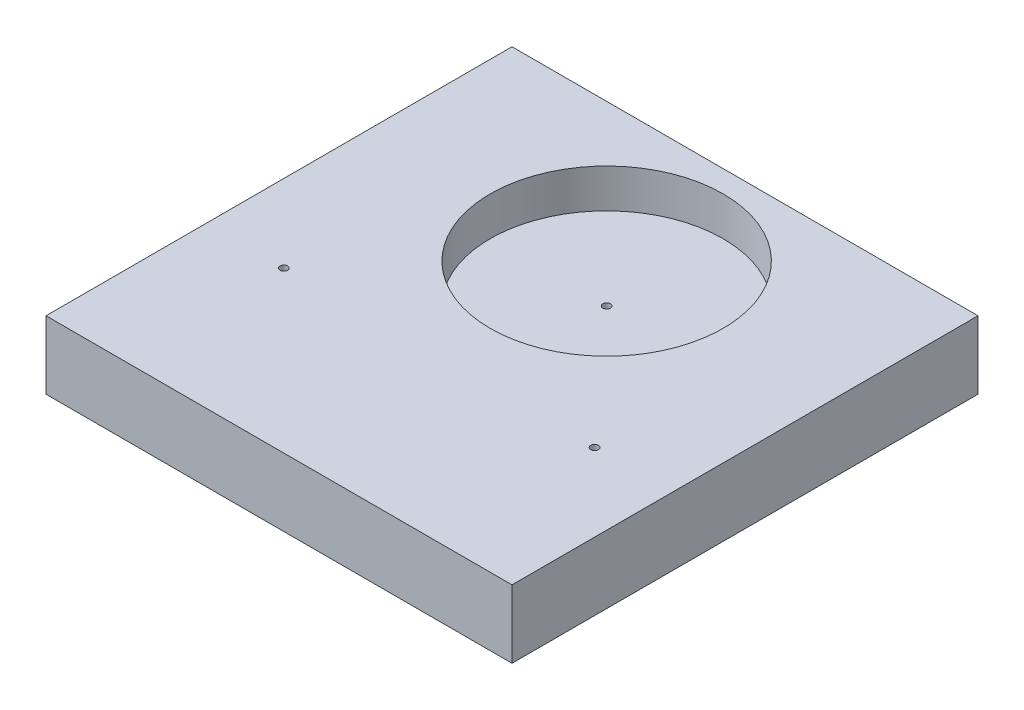
SolidWorks part; units mm, degrees
ref_plane "Front Plane" through (0, 0, 0) normal (0, 0, 1) x (1, 0, 0)
ref_plane "Top Plane" through (0, 0, 0) normal (0, 1, 0) x (1, 0, 0)
ref_plane "Right Plane" through (0, 0, 0) normal (1, 0, 0) x (0, 0, -1)
sketch "Sketch1" plane through (0, 0, 0) normal (0, 0, 1) x (1, 0, 0)
  line L7 (-76.2, -11.1125) -> (76.2, -11.1125)
  line L8 (-76.2, -11.1125) -> (-76.2, 11.1125)
  line L9 (-76.2, 11.1125) -> (76.2, 11.1125)
  line L10 (76.2, -11.1125) -> (76.2, 11.1125)
  line L11 (-76.2, -11.1125) -> (76.2, 11.1125) construction
  line L12 (-76.2, 11.1125) -> (76.2, -11.1125) construction
  point P4 (0, 0)
  point P14 (0, 0)
  dimension "Thickness" = 22.225
  dimension "Width" = 152.4
sketch "Sketch2" plane through (0, 0, 0) normal (0, 1, 0) x (0, 0, -1)
  line L0 (76.2, 76.2) -> (-76.2, 76.2) construction
  point P4 (0, 76.2)
  dimension "Length" = 152.4
sketch "Sketch3" plane through (0, 0, 0) normal (0, 0, 1) x (1, 0, 0)
  line L6 (-76.2, 11.1125) -> (76.2, 11.1125)
  line L7 (76.2, 11.1125) -> (76.2, -11.1125)
  line L8 (76.2, -11.1125) -> (-76.2, -11.1125)
  line L9 (-76.2, -11.1125) -> (-76.2, 11.1125)
extrude "Boss-Extrude1" add sketch "Sketch3" along normal mid plane 152.4
sketch "Feet" plane through (0, -11.1125, 0) normal (0, -1, 0) x (1, 0, 0)
  line L0 (-76.2, 76.2) -> (76.2, 76.2) construction
  line L1 (-76.2, 76.2) -> (-76.2, -76.2) construction
  line L2 (0, 76.2) -> (0, -76.2) construction
  line L3 (-76.2, -76.2) -> (76.2, -76.2) construction
  line L4 (-76.2, 0) -> (76.2, 0) construction
  line L5 (76.2, 76.2) -> (76.2, -76.2) construction
  circle A0 centre (-63.5, 63.5) radius 6.35
  circle A1 centre (63.5, 63.5) radius 6.35
  circle A2 centre (63.5, -63.5) radius 6.35
  circle A3 centre (-63.5, -63.5) radius 6.35
  dimension "D3" = 12.7
  dimension "D1" = 12.7
  dimension "D2" = 12.7
extrude "Rubber Feet" [suppressed] cut sketch "Feet" against normal blind 3.175
sketch "Sketch6" plane through (0, 11.1125, 0) normal (0, 1, 0) x (1, 0, 0)
  line L0 (-76.2, -76.2) -> (-76.2, -57.15) construction
  line L1 (-76.2, -76.2) -> (-76.2, 76.2) construction
  line L2 (-76.2, -57.15) -> (-63.5, -57.15) construction
  line L3 (-63.5, -57.15) -> (63.5, -57.15) construction
  line L4 (-63.5, -49.2125) -> (63.5, -49.2125)
  line L5 (-63.5, -65.0875) -> (63.5, -65.0875)
  line L6 (0, -57.15) -> (0, -76.2) construction
  line L7 (76.2, -76.2) -> (-76.2, -76.2) construction
  arc A0 (-63.5, -49.2125) -> (-63.5, -65.0875) centre (-63.5, -57.15) ccw
  arc A1 (63.5, -65.0875) -> (63.5, -49.2125) centre (63.5, -57.15) ccw
  point P5 (0, -57.15)
  dimension "D1" = 19.05
  dimension "D3" = 15.875
extrude "Cut-Extrude2" [suppressed] cut sketch "Sketch6" against normal blind 6.35
fillet "Fillet2" [suppressed] radius 6.35
fillet "Fillet1" [suppressed] radius 3.175
sketch "Sketch7" plane through (0, -11.1125, 0) normal (0, -1, 0) x (1, 0, 0)
  line L0 (-69.85, 23.8125) -> (69.85, 23.8125) construction
  line L1 (0, 11.1125) -> (0, 36.5125) construction
  line L2 (-50.8, 23.8125) -> (50.8, 23.8125) construction
  line L4 (-76.2, -76.2) -> (76.2, -76.2)
  line L5 (-76.2, -76.2) -> (76.2, -76.2)
  line L6 (76.2, -76.2) -> (76.2, 76.2)
  line L7 (76.2, -76.2) -> (76.2, 76.2)
  line L12 (69.85, 36.5125) -> (-69.85, 36.5125)
  line L13 (69.85, 11.1125) -> (69.85, 36.5125)
  line L14 (-69.85, 11.1125) -> (69.85, 11.1125)
  line L15 (-69.85, 36.5125) -> (-69.85, 11.1125)
  line L16 (69.85, 36.5125) -> (-69.85, 36.5125) construction
  line L17 (69.85, 11.1125) -> (69.85, 36.5125) construction
  line L18 (-69.85, 11.1125) -> (69.85, 11.1125) construction
  line L19 (-69.85, 36.5125) -> (-69.85, 11.1125) construction
  line L23 (76.2, 76.2) -> (-76.2, 76.2)
  line L24 (76.2, 76.2) -> (-76.2, 76.2)
  line L25 (-76.2, 76.2) -> (-76.2, -76.2)
  line L26 (-76.2, 76.2) -> (-76.2, -76.2)
  point P11 (0, 0)
  point P18 (0, 23.8125)
  dimension "D3" = 101.6
  dimension "D1" = 0
  dimension "D2" = 0
hole_wizard "M3 Tapped Hole1" positions "Sketch8" profile "Sketch9" tap size "M3" standard "DIN" end condition through all
sketch "Sketch8" plane through (0, -11.1125, 0) normal (0, -1, 0) x (-1, 0, 0)
  point P0 (-50.8, -23.8125)
  point P3 (50.8, -23.8125)
sketch "Sketch9" plane through (50.8, -11.1125, 23.8125) normal (1, 0, 0) x (0, 0, -1)
  line L0 (0, 0) -> (0, 22.225)
  line L1 (0, 22.225) -> (1.25, 22.225)
  line L2 (1.25, 22.225) -> (1.25, 0)
  line L5 (1.25, 0) -> (0, 0)
  line L11 (0, -6.35) -> (0, 107.95) construction
  dimension "Thru Tap Drill Dia." = 2.5
  dimension "Thru Tap Drill Depth" = 22.225
sketch "Sketch10" plane through (0, 11.1125, 0) normal (0, 1, 0) x (1, 0, 0)
  line L0 (-69.85, -11.1125) -> (-69.85, 73.025) construction
  line L1 (-73.025, 73.025) -> (73.025, 73.025) construction
  line L2 (-69.85, 30.9562) -> (0, 30.9562) construction
  circle A0 centre (0, 30.9562) radius 38.1
  dimension "D1" = 76.2
extrude "Cut-Extrude3" cut sketch "Sketch10" against normal blind 12.7
sketch "Sketch11" plane through (0, -11.1125, 0) normal (0, -1, 0) x (1, 0, 0)
  line L4 (-76.2, -76.2) -> (76.2, -76.2)
  line L5 (-76.2, -76.2) -> (76.2, -76.2)
  line L6 (76.2, -76.2) -> (76.2, 76.2)
  line L7 (76.2, -76.2) -> (76.2, 76.2)
  line L12 (76.2, 76.2) -> (-76.2, 76.2)
  line L13 (76.2, 76.2) -> (-76.2, 76.2)
  line L14 (-76.2, 76.2) -> (-76.2, -76.2)
  line L15 (-76.2, 76.2) -> (-76.2, -76.2)
  circle A1 centre (0, -30.9562) radius 38.1
  circle A2 centre (0, -30.9562) radius 38.1
  dimension "D1" = 0
  dimension "D2" = 0
hole_wizard "M3 Tapped Hole2" positions "Sketch12" profile "Sketch13" tap size "M3" standard "DIN" end condition through all
sketch "Sketch12" plane through (0, -11.1125, 0) normal (0, -1, 0) x (-1, 0, 0)
  point P0 (0, 30.9562)
sketch "Sketch13" plane through (0, -11.1125, -30.9562) normal (1, 0, 0) x (0, 0, -1)
  line L0 (0, 0) -> (0, 22.225)
  line L1 (0, 22.225) -> (1.25, 22.225)
  line L2 (1.25, 22.225) -> (1.25, 0.275)
  line L3 (1.25, 0.275) -> (1.525, 0)
  line L5 (1.525, 0) -> (0, 0)
  line L6 (-1.25, 0.275) -> (-1.525, 0) construction
  line L11 (0, -6.35) -> (0, 107.95) construction
  dimension "Thru Tap Drill Dia." = 2.5
  dimension "Thru Tap Drill Depth" = 22.225
  dimension "Near C'Sink Dia." = 3.05
  dimension "Near C'Sink Angle" = 90
equation "\"D1@Boss-Extrude1\" = \"Length@Sketch2\""
